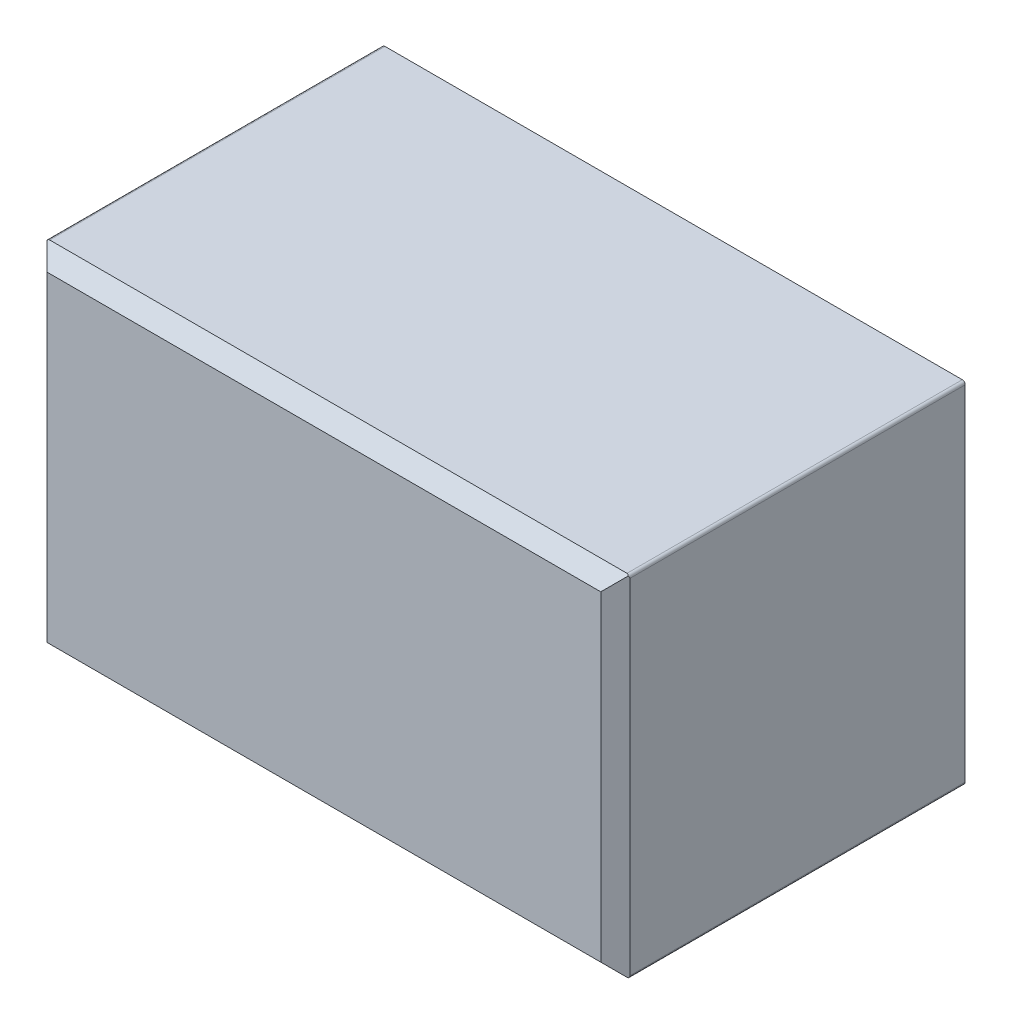
SolidWorks part; units mm, degrees
ref_plane "Front Plane" through (0, 0, 0) normal (0, 0, 1) x (1, 0, 0)
ref_plane "Top Plane" through (0, 0, 0) normal (0, 1, 0) x (1, 0, 0)
ref_plane "Right Plane" through (0, 0, 0) normal (1, 0, 0) x (0, 0, -1)
sketch "Sketch1" plane through (0, 0, 0) normal (0, 0, 1) x (1, 0, 0)
  line L1 (-1.0684, 0.6816) -> (0.9316, 0.6816)
  line L2 (-1.0684, 0.6816) -> (-1.0684, -0.5184)
  line L3 (-1.0684, -0.5184) -> (0.9316, -0.5184)
  line L4 (0.9316, 0.6816) -> (0.9316, -0.5184)
  dimension "D1" = 2
  dimension "D2" = 1.2
extrude "Boss-Extrude1" add sketch "Sketch1" along normal blind 1.2
chamfer "Chamfer1" distance 0.05 angle 45 4 edges at (0.9316, 0.0816, 1.2) (-0.0684, 0.6816, 1.2) (-1.0684, 0.0816, 1.2) (-0.0684, -0.5184, 1.2)
fillet "Fillet1" radius 0.01 4 edges at (-1.0684, -0.5184, 0.575) (-1.0684, 0.6816, 0.575) (0.9316, 0.6816, 0.575) (0.9316, -0.5184, 0.575)
